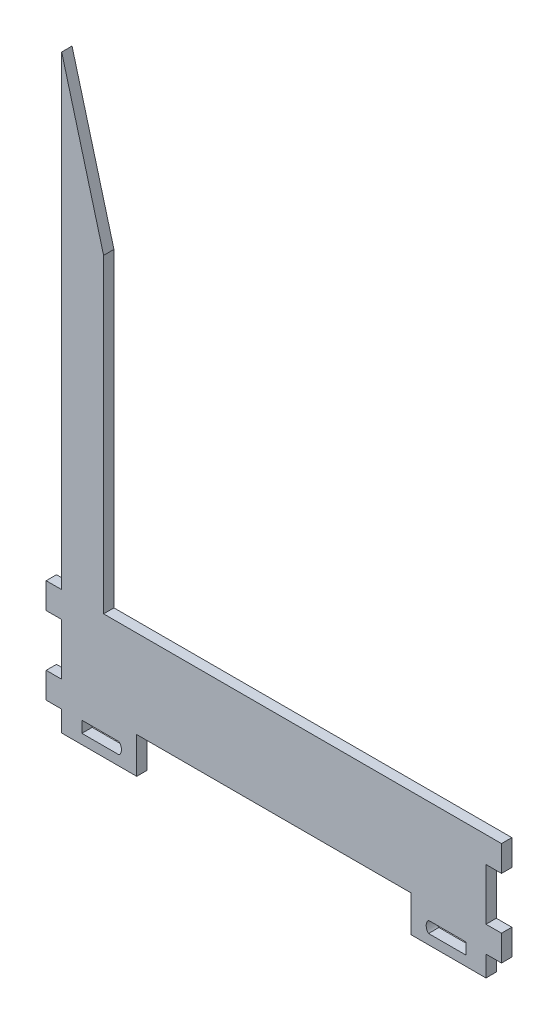
SolidWorks part; units mm, degrees
ref_plane "前视基准面" through (0, 0, 0) normal (0, 0, 1) x (1, 0, 0)
ref_plane "上视基准面" through (0, 0, 0) normal (0, 1, 0) x (1, 0, 0)
ref_plane "右视基准面" through (0, 0, 0) normal (1, 0, 0) x (0, 0, -1)
sketch "草图3" plane through (0, 0, 0) normal (0, 0, 1) x (1, 0, 0)
  line L0 (-37, -1.9902) -> (-37, -2.0902) construction
  line L2 (-41, -1.9902) -> (-41, 0.0098) construction
  line L4 (41, -1.9902) -> (41, 0.0098) construction
  line L5 (-37, 0.0098) -> (-30, 0.0098) construction
  line L6 (-37, 0.0098) -> (-37, -1.9902) construction
  line L7 (-37, -1.9902) -> (-30, -1.9902) construction
  line L8 (-30, 0.0098) -> (-30, -1.9902) construction
  line L9 (-37, -2.0902) -> (-37.1, -2.0902) construction
  line L10 (41, 20.0098) -> (-32.9, 20.0098)
  line L11 (30, 0.0098) -> (37, 0.0098) construction
  line L12 (30, 0.0098) -> (30, -1.9902) construction
  line L13 (30, -1.9902) -> (37, -1.9902) construction
  line L14 (37, 0.0098) -> (37, -1.9902) construction
  line L17 (-32.9, 20.0098) -> (-32.9, 80.0098)
  line L19 (-37.1, -2.0902) -> (-29.9, -2.0902)
  line L20 (-37.1, -2.0902) -> (-37.1, 0.1098)
  line L21 (-37.1, 0.1098) -> (-29.9, 0.1098)
  line L24 (37.1, -2.0902) -> (29.9, -2.0902)
  line L25 (37.1, -2.0902) -> (37.1, 0.1098)
  line L26 (37.1, 0.1098) -> (29.9, 0.1098)
  line L27 (-41, 0.0098) -> (-41, -3.9902)
  line L30 (41, 0.0098) -> (41, -3.9902)
  line L33 (-26.5, 3.0098) -> (26.5, 3.0098)
  line L39 (-41, 0.0098) -> (-44, 0.0098)
  line L40 (-44, 0.0098) -> (-44, 5.0098)
  line L41 (-44, 5.0098) -> (-41, 5.0098)
  line L53 (-41, 5.0098) -> (-41, 7.0098)
  line L54 (-41, 10.0098) -> (-41, 15.0098)
  line L55 (-41, 15.0098) -> (-44, 15.0098)
  line L56 (-44, 15.0098) -> (-44, 20.0098)
  line L57 (-44, 20.0098) -> (-41, 20.0098)
  line L58 (-41, 20.0098) -> (-41, 60.0098)
  line L59 (44, 20.0098) -> (41, 20.0098)
  line L60 (44, 15.0098) -> (44, 20.0098)
  line L61 (41, 15.0098) -> (44, 15.0098)
  line L62 (41, 10.0098) -> (41, 15.0098)
  line L63 (41, 5.0098) -> (41, 7.0098)
  line L75 (44, 5.0098) -> (41, 5.0098)
  line L76 (41, 0.0098) -> (44, 0.0098)
  line L77 (44, 0.0098) -> (44, 5.0098)
  line L78 (-32.9, 80.0098) -> (-41, 110.0011)
  line L79 (-41, 110.0011) -> (-41, 60.0098)
  line L81 (41, -3.9902) -> (26.5, -3.9902)
  line L82 (26.5, -3.9902) -> (26.5, 3.0098)
  line L83 (-26.5, 3.0098) -> (-26.5, -3.9902)
  line L84 (-26.5, -3.9902) -> (-41, -3.9902)
  line L85 (41, 10.0098) -> (41, 7.0098)
  line L86 (-41, 10.0098) -> (-41, 7.0098)
  arc A2 (29.9, 0.1098) -> (29.9, -2.0902) centre (31, -0.9902) ccw
  arc A3 (-29.9, -2.0902) -> (-29.9, 0.1098) centre (-31, -0.9902) ccw
extrude "凸台-拉伸1" add sketch "草图3" along normal blind 2
